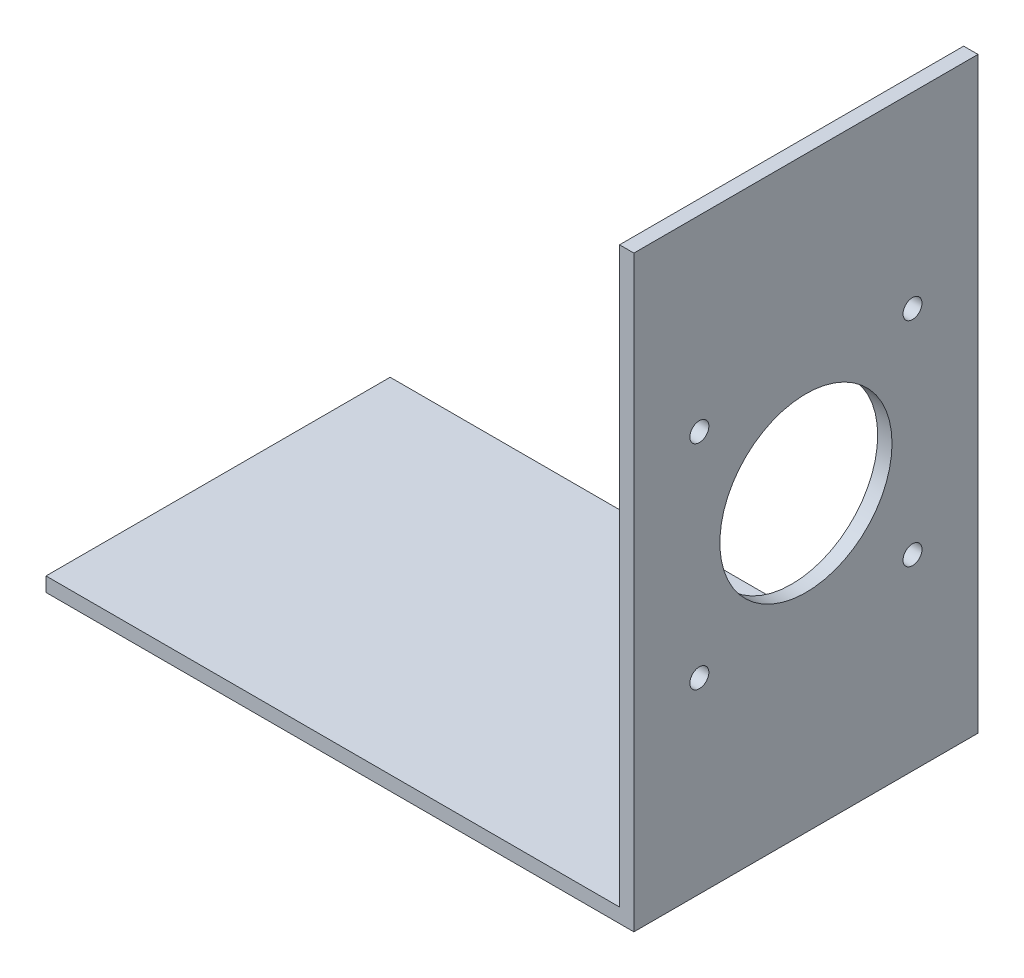
SolidWorks part; units mm, degrees
ref_plane "Front Plane" through (0, 0, 0) normal (0, 0, 1) x (1, 0, 0)
ref_plane "Top Plane" through (0, 0, 0) normal (0, 1, 0) x (1, 0, 0)
ref_plane "Right Plane" through (0, 0, 0) normal (1, 0, 0) x (0, 0, -1)
sketch "Sketch1" plane through (0, 0, 0) normal (0, 0, 1) x (1, 0, 0)
  line L0 (0, 0) -> (127, 0)
  line L1 (127, 0) -> (127, 127)
  dimension "D1" = 127
  dimension "D2" = 127
extrude "Extrude-Thin1" add sketch "Sketch1" along normal blind 76.2 thin
hole_wizard "Tap Drill for M5x0.8 Tap1" positions "Sketch2" profile "Sketch3" hole size "M5x0.8" standard "ANSI Metric"
sketch "Sketch2" plane through (130.175, 0, 0) normal (1, 0, 0) x (0, 0, -1)
  line L1 (-61.7, 38.3125) -> (-14.5, 38.3125)
  line L2 (-61.7, 38.3125) -> (-61.7, 85.5125)
  line L3 (-61.7, 85.5125) -> (-14.5, 85.5125)
  line L4 (-14.5, 38.3125) -> (-14.5, 85.5125)
  line L5 (-61.7, 38.3125) -> (-14.5, 85.5125) construction
  line L6 (-61.7, 85.5125) -> (-14.5, 38.3125) construction
  line L7 (-38.1, 127) -> (-38.1, -3.175) construction
  line L8 (-76.2, 127) -> (0, 127) construction
  line L9 (-76.2, -3.175) -> (0, -3.175) construction
  point P2 (-14.5, 85.5125)
  point P91 (-61.7, 38.3125)
  point P92 (-61.7, 85.5125)
  point P93 (-14.5, 38.3125)
  point P115 (-38.1, 61.9125)
  dimension "D1" = 47.2
  dimension "D2" = 47.2
sketch "Sketch3" plane through (130.175, 85.5125, 14.5) normal (0, 1, 0) x (0, 0, -1)
  line L0 (0, 0) -> (0, 13.1998)
  line L1 (0, 13.1998) -> (2.1, 11.938)
  line L2 (2.1, 11.938) -> (2.1, 0)
  line L5 (2.1, 0) -> (0, 0)
  line L10 (0, 13.1998) -> (-2.1, 11.938) construction
  line L11 (0, -6.35) -> (0, 107.95) construction
  dimension "Hole Dia." = 4.2
  dimension "Hole Depth" = 11.938
  dimension "Drill Angle" = 118
sketch "Sketch4" plane through (130.175, 0, 0) normal (1, 0, 0) x (0, 0, -1)
  line L0 (-38.1, 127) -> (-38.1, -3.175) construction
  line L1 (-76.2, 127) -> (0, 127) construction
  line L2 (-76.2, -3.175) -> (0, -3.175) construction
  circle A0 centre (-38.1, 61.9125) radius 19.0627
  dimension "D1" = 38.1254
extrude "Cut-Extrude1" cut sketch "Sketch4" against normal through all
equation "\"D2@Sketch2\"=\"D1@Sketch2\""
equation "\"D1@Sketch1\"=\"D2@Sketch1\""
